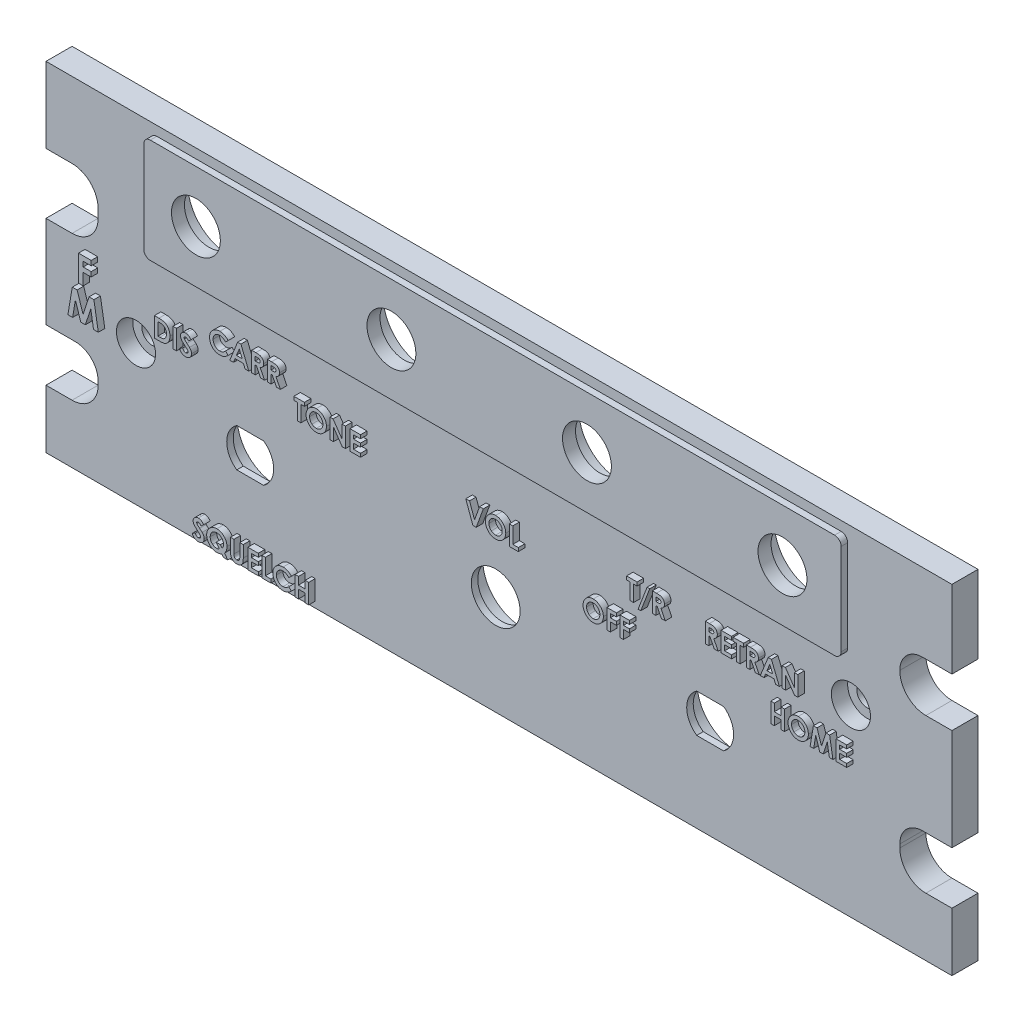
SolidWorks part; units mm, degrees
ref_plane "Front Plane" through (0, 0, 0) normal (0, 0, 1) x (1, 0, 0)
ref_plane "Top Plane" through (0, 0, 0) normal (0, 1, 0) x (1, 0, 0)
ref_plane "Right Plane" through (0, 0, 0) normal (1, 0, 0) x (0, 0, -1)
sketch "Sketch1" plane through (0, 0, 0) normal (0, 0, 1) x (1, 0, 0)
  line L1 (0, 0) -> (131, 0)
  line L5 (69.5, 52) -> (69.5, 0) construction
  line L6 (8, 52) -> (8, 0) construction
  line L11 (131, 52) -> (131, 0) construction
  line L21 (8, 52) -> (131, 52)
  line L22 (0, 0) -> (131, 0) construction
  line L23 (0, 0) -> (0, 11) construction
  line L25 (0, 0.5505) -> (0, 64.6609) construction
  line L28 (0, 8.9702) -> (4, 8.9702)
  line L30 (4.5, 17) -> (0, 17)
  line L33 (0, 17) -> (0, 8.9702) construction
  line L35 (134.5, 17) -> (139, 17)
  line L37 (139, 8.9702) -> (135, 8.9702)
  line L40 (131, 13.5) -> (131, 12.9702)
  line L47 (8, 0) -> (131, 0)
  line L48 (99.8397, 12.3516) -> (103.9664, 12.3516) construction
  line L49 (103.9664, 18.2516) -> (99.8397, 18.2516) construction
  line L50 (29.2679, 12.3516) -> (33.3946, 12.3516) construction
  line L51 (33.3946, 18.2516) -> (29.2679, 18.2516) construction
  line L52 (99.8397, 12.3516) -> (103.9664, 12.3516)
  line L53 (103.9664, 18.2516) -> (99.8397, 18.2516)
  line L54 (29.2679, 12.3516) -> (33.3946, 12.3516)
  line L55 (33.3946, 18.2516) -> (29.2679, 18.2516)
  line L56 (139, 32.5742) -> (135, 32.5742)
  line L57 (139, -1) -> (139, 196.5) construction
  line L58 (134.5, 40.0742) -> (139, 40.0742)
  line L59 (131, 52) -> (139, 52)
  line L60 (139, 52) -> (139, 40.0742)
  line L61 (139, 32.5742) -> (139, 17)
  line L62 (139, 8.9702) -> (139, 0)
  line L63 (139, 0) -> (131, 0)
  line L64 (8, 13.5) -> (8, 12.9702)
  line L65 (8, 52) -> (0, 52)
  line L66 (0, 52) -> (0, 40.4248)
  line L67 (0, 8.9702) -> (0, 0)
  line L68 (0, 40.4248) -> (4, 40.4248)
  line L69 (8, 36.4248) -> (8, 35.1407)
  line L70 (4, 31.1407) -> (0, 31.1407)
  line L71 (0, 31.1407) -> (0, 17)
  line L72 (138.5, 52) -> (-0.5, 52) construction
  circle A14 centre (13.8091, 21.5) radius 1.6 construction
  arc A15 (99.8397, 18.2516) -> (99.8397, 12.3516) centre (101.903, 15.3016) ccw construction
  circle A16 centre (4, 16) radius 1.6 construction
  circle A17 centre (4, 38) radius 1.6 construction
  arc A26 (29.2679, 18.2516) -> (29.2679, 12.3516) centre (31.3312, 15.3016) ccw construction
  arc A27 (33.3946, 12.3516) -> (33.3946, 18.2516) centre (31.3312, 15.3016) ccw construction
  circle A28 centre (69, 15.3016) radius 3.75 construction
  arc A29 (103.9664, 12.3516) -> (103.9664, 18.2516) centre (101.903, 15.3016) ccw construction
  circle A30 centre (123.5, 28.1942) radius 1.6 construction
  circle A31 centre (114, 42.5415) radius 3.75 construction
  circle A32 centre (84, 42.5415) radius 3.75 construction
  circle A33 centre (54, 42.5415) radius 3.75 construction
  arc A49 (8, 12.9702) -> (4, 8.9702) centre (4, 12.9702) cw
  arc A50 (8, 13.5) -> (4.5, 17) centre (4.5, 13.5) ccw
  arc A53 (131, 13.5) -> (134.5, 17) centre (134.5, 13.5) cw
  arc A54 (131, 12.9702) -> (135, 8.9702) centre (135, 12.9702) ccw
  circle A65 centre (3.5, 13.5) radius 1.6 construction
  circle A66 centre (3.5, 35.5) radius 1.6 construction
  circle A67 centre (134.5, 13.5) radius 1.6 construction
  circle A68 centre (134.5, 35.5) radius 1.6 construction
  circle A69 centre (3.5, 13.5) radius 1.6 construction
  circle A70 centre (3.5, 35.5) radius 1.6 construction
  circle A71 centre (134.5, 13.5) radius 1.6 construction
  circle A72 centre (134.5, 35.5) radius 1.6 construction
  circle A73 centre (24, 42.5415) radius 3.75 construction
  circle A74 centre (13.8091, 21.5) radius 1.6
  arc A75 (99.8397, 18.2516) -> (99.8397, 12.3516) centre (101.903, 15.3016) ccw
  arc A76 (29.2679, 18.2516) -> (29.2679, 12.3516) centre (31.3312, 15.3016) ccw
  arc A77 (33.3946, 12.3516) -> (33.3946, 18.2516) centre (31.3312, 15.3016) ccw
  circle A78 centre (69, 15.3016) radius 3.75
  arc A79 (103.9664, 12.3516) -> (103.9664, 18.2516) centre (101.903, 15.3016) ccw
  circle A80 centre (123.5, 28.1942) radius 1.6
  circle A81 centre (114, 42.5415) radius 3.75
  circle A82 centre (84, 42.5415) radius 3.75
  circle A83 centre (54, 42.5415) radius 3.75
  circle A84 centre (24, 42.5415) radius 3.75
  arc A85 (131, 36.5742) -> (135, 32.5742) centre (135, 36.5742) ccw
  arc A86 (131, 36.5742) -> (134.5, 40.0742) centre (134.5, 36.5742) cw
  arc A87 (8, 35.1407) -> (4, 31.1407) centre (4, 35.1407) cw
  arc A88 (4, 40.4248) -> (8, 36.4248) centre (4, 36.4248) cw
  point P22 (8, 32.5915)
  point P67 (8, 17)
  point P90 (8, 31.1407)
  point P96 (8, 40.4248)
  dimension "D3" = 4
  dimension "D4" = 8
  dimension "D5" = 4
  dimension "D8" = 29.0298
  dimension "D12" = 22
  dimension "D6" = 4
  dimension "D10" = 3.5
  dimension "D1" = 123
  dimension "D2" = 52
  dimension "D7" = 1
extrude "Extrusion base" add sketch "Sketch1" along normal blind 4
sketch "Sketch5" plane through (0, 0, 4) normal (0, 0, 1) x (1, 0, 0)
  line L1 (122, 34.5415) -> (17, 34.5415)
  line L2 (123, 35.5415) -> (123, 49.5415)
  line L3 (122, 50.5415) -> (17, 50.5415)
  line L4 (16, 35.5415) -> (16, 49.5415)
  line L6 (0, 52) -> (0, 40.4248) construction
  line L7 (139, 52) -> (139, 40.0742) construction
  circle A0 centre (114, 42.5415) radius 3.75 construction
  circle A1 centre (84, 42.5415) radius 3.75 construction
  circle A2 centre (54, 42.5415) radius 3.75 construction
  circle A3 centre (24, 42.5415) radius 3.75 construction
  circle A4 centre (114, 42.5415) radius 3.75
  circle A5 centre (84, 42.5415) radius 3.75
  circle A6 centre (54, 42.5415) radius 3.75
  circle A7 centre (24, 42.5415) radius 3.75
  arc A8 (17, 34.5415) -> (16, 35.5415) centre (17, 35.5415) cw
  arc A9 (17, 50.5415) -> (16, 49.5415) centre (17, 49.5415) ccw
  arc A10 (122, 34.5415) -> (123, 35.5415) centre (122, 35.5415) ccw
  arc A11 (123, 49.5415) -> (122, 50.5415) centre (122, 49.5415) ccw
  dimension "D5" = 1
  dimension "D1" = 8
  dimension "D2" = 8
  dimension "D3" = 16
  dimension "D4" = 16
extrude "Boss-Extrude1" add sketch "Sketch5" along normal blind 1
sketch "Sketch6" plane through (0, 0, 0) normal (0, 0, -1) x (-1, 0, 0)
  arc A0 (-99.8397, 12.3516) -> (-99.8397, 18.2516) centre (-101.903, 15.3016) ccw construction
  circle A1 centre (-69, 15.3016) radius 3.75 construction
  arc A2 (-29.2679, 12.3516) -> (-29.2679, 18.2516) centre (-31.3312, 15.3016) ccw construction
  circle A3 centre (-24, 42.5415) radius 3.75 construction
  circle A4 centre (-54, 42.5415) radius 3.75 construction
  circle A5 centre (-84, 42.5415) radius 3.75 construction
  circle A6 centre (-114, 42.5415) radius 3.75 construction
  circle A7 centre (-101.903, 15.3016) radius 3.6 construction
  circle A8 centre (-69, 15.3016) radius 3.75 construction
  circle A9 centre (-31.3312, 15.3016) radius 3.6 construction
  circle A10 centre (-24, 42.5415) radius 3.75 construction
  circle A11 centre (-54, 42.5415) radius 3.75 construction
  circle A12 centre (-84, 42.5415) radius 3.75 construction
  circle A13 centre (-114, 42.5415) radius 3.75 construction
  circle A14 centre (-114, 42.5415) radius 6.25
  circle A15 centre (-84, 42.5415) radius 6.25
  circle A16 centre (-54, 42.5415) radius 6.25
  circle A17 centre (-24, 42.5415) radius 6.25
  circle A18 centre (-31.3312, 15.3016) radius 6
  circle A19 centre (-69, 15.3016) radius 6
  circle A20 centre (-101.903, 15.3016) radius 6
  dimension "D1" = 12.5
  dimension "D2" = 12
extrude "Back Holes" cut sketch "Sketch6" against normal blind 3
sketch "Sketch7" plane through (0, 0, 4) normal (0, 0, 1) x (1, 0, 0)
  circle A2 centre (13.8091, 21.5) radius 3
  circle A3 centre (123.5, 28.1942) radius 3
  dimension "D1" = 6
extrude "Cut-Extrude2" cut sketch "Sketch7" against normal blind 2.5
sketch "Sketch4" plane through (0, 0, 4) normal (0, 0, 1) x (1, 0, 0)
  line L0 (7.2544, 26.9631) -> (7.2544, 14.5758) construction
  line L3 (-3.8412, 26.0104) -> (13.9628, 26.0104) construction
  line L4 (-4.2039, 21.0104) -> (13.9628, 21.0104) construction
  line L6 (4.2544, 33.1522) -> (4.2544, -6.1206) construction
  text T0 "<b>F</b>" font "Century Gothic" height 4
  text T1 "<b>CARR</b>" font "Century Gothic" height 3
  text T2 "<b>TONE</b>" font "Century Gothic" height 3
  text T3 "<b>OFF</b>" font "Century Gothic" height 3
  text T4 "<b>DIS</b>" font "Century Gothic" height 3
  text T5 "<b>VOL</b>" font "Century Gothic" height 3
  text T6 "<b>RETRAN</b>" font "Century Gothic" height 3
  text T7 "<b>M</b>" font "Century Gothic" height 4
  text T8 "<b>HOME</b>" font "Century Gothic" height 3
  text T9 "<b>T/R</b>" font "Century Gothic" height 3
  text T10 "<b>SQUELCH</b>" font "Century Gothic" height 3
  dimension "D1" = 5
  dimension "D3" = 3
extrude "Textos" add sketch "Sketch4" along normal blind 1
